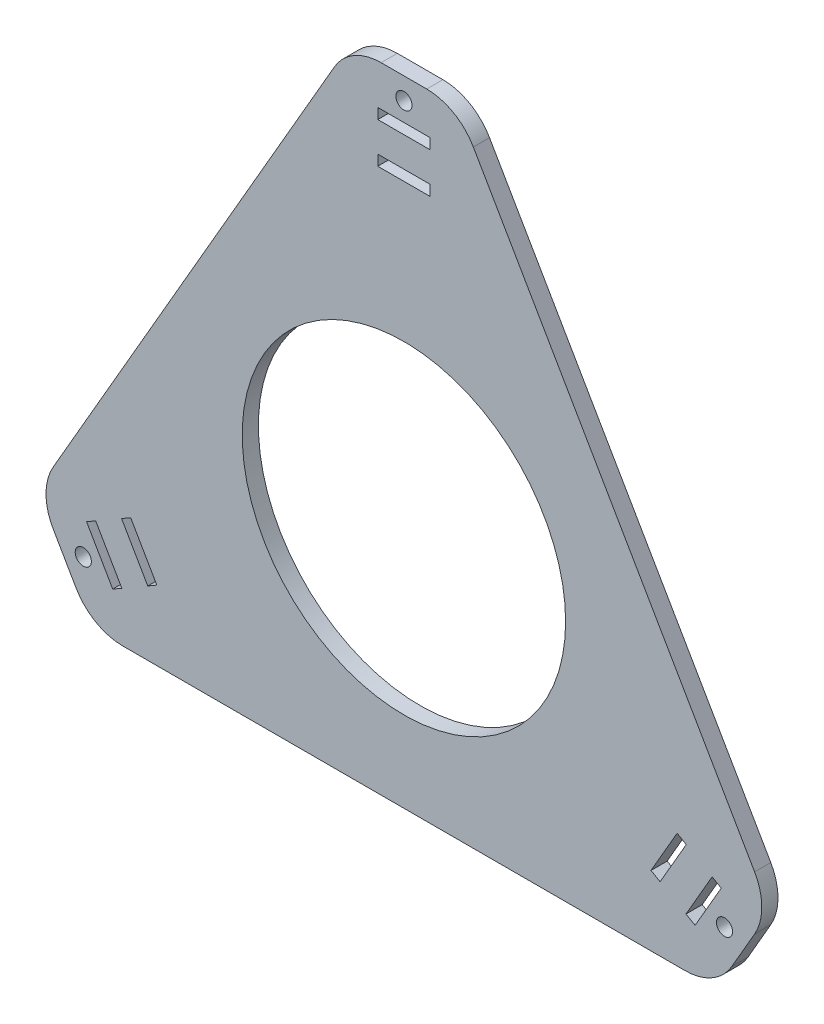
SolidWorks part; units mm, degrees
ref_plane "Спереди" through (0, 0, 0) normal (0, 0, 1) x (1, 0, 0)
ref_plane "Сверху" through (0, 0, 0) normal (0, 1, 0) x (1, 0, 0)
ref_plane "Справа" through (0, 0, 0) normal (1, 0, 0) x (0, 0, -1)
other "Configuration Table"
sketch "Эскиз1" plane through (0, 0, 0) normal (0, 0, 1) x (1, 0, 0)
  line L0 (0, 0) -> (-111.2054, -64.2045) construction
  line L1 (-52.1688, -45) -> (52.1688, -45)
  line L2 (65.0555, -22.6795) -> (12.8868, 67.6795)
  line L3 (-12.8868, 67.6795) -> (-65.0555, -22.6795)
  line L4 (-54.0221, -36.79) -> (-58.8721, -28.3895)
  line L6 (-65.0555, -32.6795) -> (-60.829, -40)
  line L7 (65.0555, -32.6795) -> (60.829, -40)
  line L8 (4.2265, 72.6795) -> (-4.2265, 72.6795)
  line L12 (0, 0) -> (62.9423, -36.3397) construction
  line L13 (-54.0221, -36.79) -> (-52.3333, -35.815)
  line L14 (-58.8721, -28.3895) -> (-57.1833, -27.4145)
  line L15 (-52.3333, -35.815) -> (-57.1833, -27.4145)
  line L16 (-54.0221, -36.79) -> (-57.1833, -27.4145) construction
  line L17 (-58.8721, -28.3895) -> (-52.3333, -35.815) construction
  line L18 (-4.85, 65.1795) -> (-4.85, 63.2295)
  line L19 (4.85, 63.2295) -> (-4.85, 63.2295)
  line L20 (4.85, 65.1795) -> (4.85, 63.2295)
  line L21 (4.85, 65.1795) -> (-4.85, 65.1795)
  line L22 (58.8721, -28.3895) -> (54.0221, -36.79)
  line L23 (58.8721, -28.3895) -> (57.1833, -27.4145)
  line L24 (57.1833, -27.4145) -> (52.3333, -35.815)
  line L25 (54.0221, -36.79) -> (52.3333, -35.815)
  line L26 (-47.5269, -33.04) -> (-52.3769, -24.6395)
  line L27 (-47.5269, -33.04) -> (-45.8382, -32.065)
  line L28 (-52.3769, -24.6395) -> (-50.6882, -23.6645)
  line L29 (-45.8382, -32.065) -> (-50.6882, -23.6645)
  line L30 (4.85, 57.6795) -> (4.85, 55.7295)
  line L31 (4.85, 55.7295) -> (-4.85, 55.7295)
  line L32 (-4.85, 57.6795) -> (-4.85, 55.7295)
  line L33 (4.85, 57.6795) -> (-4.85, 57.6795)
  line L34 (52.3769, -24.6395) -> (47.5269, -33.04)
  line L35 (47.5269, -33.04) -> (45.8382, -32.065)
  line L36 (50.6882, -23.6645) -> (45.8382, -32.065)
  line L37 (52.3769, -24.6395) -> (50.6882, -23.6645)
  circle A0 centre (0, 0) radius 45 construction
  circle A1 centre (-59.4782, -34.3397) radius 1.5
  circle A2 centre (0, 68.6795) radius 1.5
  circle A3 centre (59.4782, -34.3397) radius 1.5
  circle A4 centre (0, 0) radius 30
  arc A5 (-52.1688, -45) -> (-60.829, -40) centre (-52.1688, -35) cw
  arc A6 (-65.0555, -32.6795) -> (-65.0555, -22.6795) centre (-56.3953, -27.6795) cw
  arc A7 (-4.2265, 72.6795) -> (-12.8868, 67.6795) centre (-4.2265, 62.6795) ccw
  arc A8 (4.2265, 72.6795) -> (12.8868, 67.6795) centre (4.2265, 62.6795) cw
  arc A9 (65.0555, -22.6795) -> (65.0555, -32.6795) centre (56.3953, -27.6795) cw
  arc A10 (60.829, -40) -> (52.1688, -45) centre (52.1688, -35) cw
  point P4 (-55.6027, -32.1022)
  point P9 (-62.9423, -36.3397)
  point P16 (-57.9423, -45)
  point P49 (-67.9423, -27.6795)
  point P52 (-10, 72.6795)
  point P55 (10, 72.6795)
  point P58 (67.9423, -27.6795)
  point P61 (57.9423, -45)
  point P62 (0, 0)
  point P63 (0, 0)
  dimension "D5" = 3
  dimension "D12" = 60
  dimension "D13" = 10
  dimension "D14" = 10
  dimension "D2" = 90
  dimension "D1" = 20
  dimension "D3" = 1.95
  dimension "D4" = 20
  dimension "D6" = 9.7
  dimension "D7" = 4
  dimension "D8" = 20
  dimension "D9" = 3.5
  dimension "D10" = 5.55
  dimension "D11" = 1.95
extrude "Бобышка-Вытянуть1" add sketch "Эскиз1" along normal blind 3
